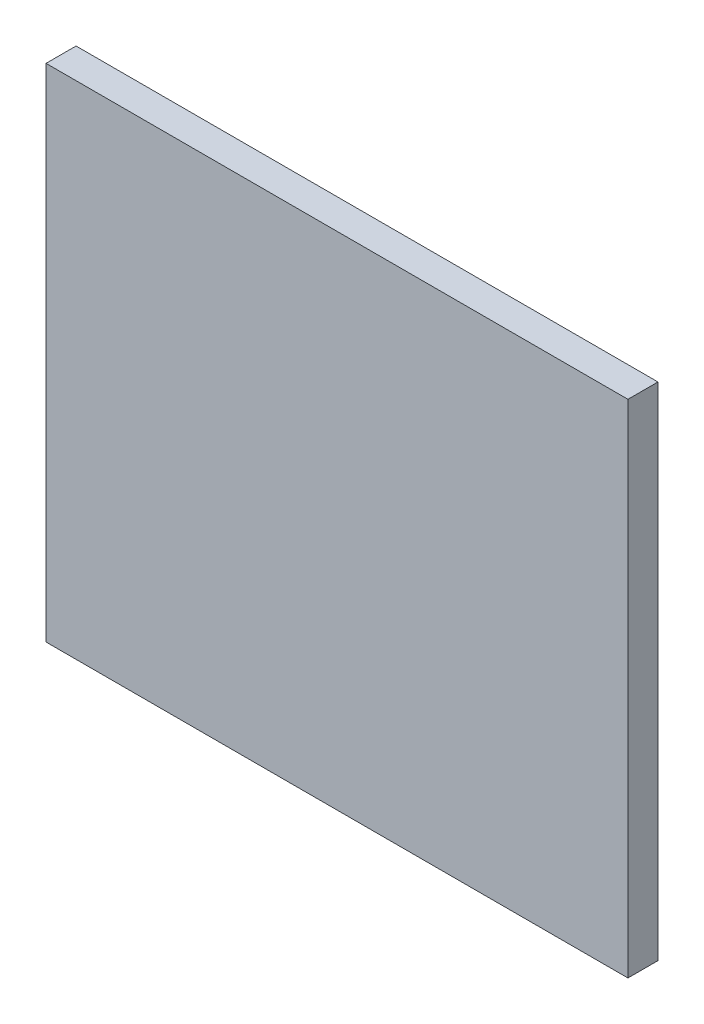
SolidWorks part; units mm, degrees
ref_plane "Horní rovina" through (0, 0, 0) normal (0, 0, 1) x (1, 0, 0)
ref_plane "Přední rovina" through (0, 0, 0) normal (0, 1, 0) x (1, 0, 0)
ref_plane "Pravá rovina" through (0, 0, 0) normal (1, 0, 0) x (0, 0, -1)
sketch "Skica1" plane through (0, 0, 0) normal (0, 0, 1) x (1, 0, 0)
  line L1 (-15.5, 13.35) -> (15.5, 13.35)
  line L2 (-15.5, 13.35) -> (-15.5, -13.35)
  line L3 (-15.5, -13.35) -> (15.5, -13.35)
  line L4 (15.5, 13.35) -> (15.5, -13.35)
  line L5 (-15.5, 13.35) -> (15.5, -13.35) construction
  line L6 (-15.5, -13.35) -> (15.5, 13.35) construction
  point P0 (0, 0)
  dimension "D1" = 26.7
  dimension "D2" = 31
extrude "Přidat vysunutím1" add sketch "Skica1" along normal blind 1.6
